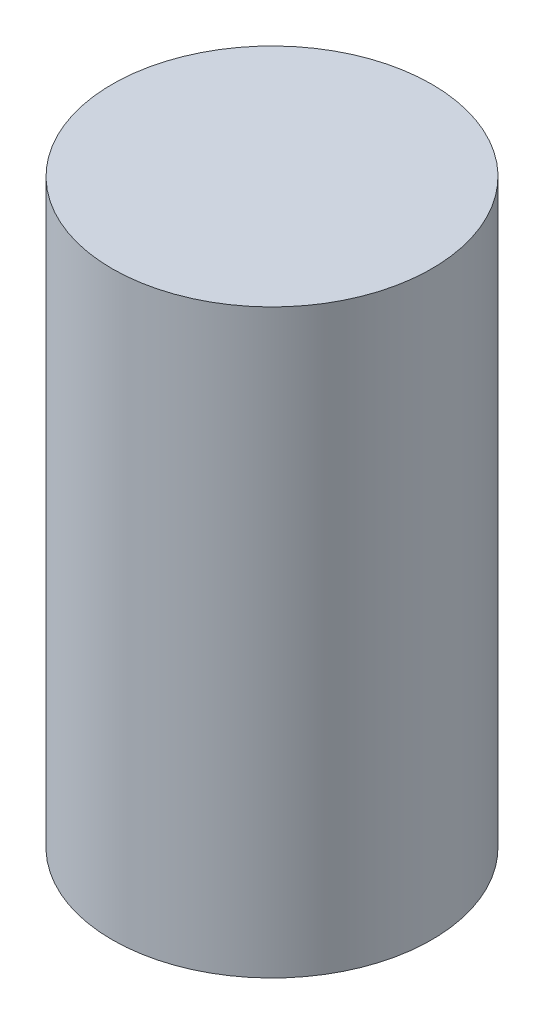
SolidWorks part; units mm, degrees
material "LAB 1 FEA"
ref_plane "Front Plane" through (0, 0, 0) normal (0, 0, 1) x (1, 0, 0)
ref_plane "Top Plane" through (0, 0, 0) normal (0, 1, 0) x (1, 0, 0)
ref_plane "Right Plane" through (0, 0, 0) normal (1, 0, 0) x (0, 0, -1)
sketch "Sketch1" plane through (0, 0, 0) normal (0, 1, 0) x (1, 0, 0)
  circle A0 centre (0, 0) radius 13.75
  point P2 (0, 0)
  dimension "D1" = 27.5
extrude "Boss-Extrude1" add sketch "Sketch1" along normal blind 50
